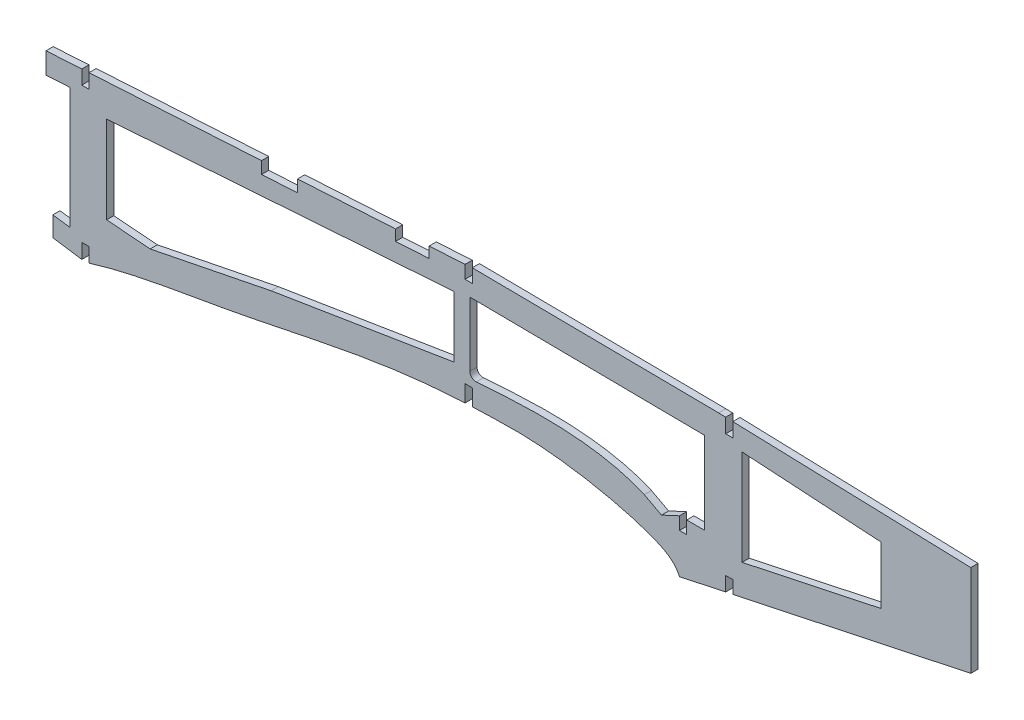
SolidWorks part; units mm, degrees
ref_plane "Front Plane" through (0, 0, 0) normal (0, 0, 1) x (1, 0, 0)
ref_plane "Top Plane" through (0, 0, 0) normal (0, 1, 0) x (1, 0, 0)
ref_plane "Right Plane" through (0, 0, 0) normal (1, 0, 0) x (0, 0, -1)
sketch "Sketch1" plane through (0, 0, 0) normal (0, 0, 1) x (1, 0, 0)
  line L0 (0, 0) -> (110, 0) construction
  line L1 (110, 0) -> (110, 21) construction
  line L2 (0, 0) -> (110, 21)
  line L3 (23.5, 17.3139) -> (20, 16.6457)
  line L4 (0, 0) -> (20, 0)
  line L5 (20, 0) -> (20, 67.15) construction
  line L6 (0, 0) -> (0, 67.15) construction
  line L7 (0, 67.15) -> (110, 67.15) construction
  line L8 (110, 61.55) -> (110, 67.15)
  line L9 (0, 67.15) -> (110, 61.55)
  line L10 (23.5, 53.9381) -> (81.5, 50.9854)
  line L11 (81.5, 50.9854) -> (81.5, 28.3866)
  line L12 (23.5, 53.9381) -> (23.5, 17.3139)
  line L13 (23.5, 17.3139) -> (81.5, 28.3866)
  line L14 (110, 21) -> (110, 61.55) construction
  line L15 (112, 61.4482) -> (112, 21.3818)
  line L16 (110, 61.55) -> (112, 61.4482)
  line L17 (110, 21) -> (112, 21.3818)
  line L18 (10.9, 67.15) -> (10.9, 0)
  line L19 (0, 67.15) -> (-82.3902, 71.3444)
  line L20 (0, 0) -> (-182.0672, -34.7583)
  line L21 (-86.7, -36.2944) -> (-86.7, -57.7944)
  line L22 (-93.05, 89.1409) -> (-93.05, -40.6456)
  line L23 (-70.5516, 60.184) -> (7.4462, 55.0566)
  line L24 (-89.4413, 54.3923) -> (-89.4413, 37.6042)
  line L25 (-65.3332, 22.0194) -> (-42.2468, 20.2821) construction
  line L26 (-42.2468, 20.2821) -> (-21.4079, 14.5616) construction
  line L27 (-21.4079, 14.5616) -> (-8.5368, 8.8411) construction
  line L28 (-8.5368, 8.8411) -> (-2.8162, 7.0023) construction
  line L29 (-2.8162, 7.0023) -> (0, 0) construction
  line L30 (-235.9653, 18.0968) -> (-234.0715, 53.1142)
  line L31 (-238.05, 59.4719) -> (-238.05, 21) construction
  line L32 (-921.7383, -124.7627) -> (144.2786, -161.9889) construction
  line L34 (-226.3459, 60.184) -> (-104.3294, 60.184)
  line L35 (-82.0567, 37.6042) -> (-82.7237, 57.9466)
  line L36 (-82.3902, 71.3444) -> (-103.6, 72.4242)
  line L37 (-103.6, 72.4242) -> (-103.6, 67.1242)
  line L38 (-103.6, 67.1242) -> (-117.6, 67.1242)
  line L39 (-117.6, 67.1242) -> (-117.6, 72.6011)
  line L40 (-117.6, 72.6011) -> (-158.5, 72.6011)
  line L41 (-158.5, 72.6011) -> (-158.5, 68.6011)
  line L42 (-158.5, 68.6011) -> (-173.5, 69.3647)
  line L43 (-173.5, 69.3647) -> (-173.5, 73.3311)
  line L44 (-173.5, 73.3311) -> (-250.6778, 73.3311)
  line L45 (-250.6778, 73.3311) -> (-251.1351, 64.35)
  line L46 (-251.1351, 64.35) -> (-249.1426, 59.4719)
  line L47 (-249.1426, 59.4719) -> (-253.0614, 11.9612)
  spline_without_curve S0
  spline S1 degree 3 poles (-62.7428, 33.1676) (-50.008, 31.9642) (-31.0962, 32.5015) (-14.1751, 24.9914) (-9.6822, 22.192) knots 0 0 0 0 0.709755 1 1 1 1
  spline S2 degree 3 poles (-9.6822, 22.192) (-6.8917, 20.9668) (-4.0654, 23.2801) (1.077, 24.0309) (6.7349, 23.1276) (13.0796, 25.9871) (10.9, 30.3114) knots 0 0 0 0 0.304362 0.391412 0.603771 1 1 1 1
  spline S3 degree 3 poles (-65.3332, 22.0194) (-77.4805, 22.6509) (-98.8967, 23.1079) (-139.7694, 19.7032) (-187.7649, 10.9991) (-227.3069, 7.5749) (-246.6861, 2.6333) knots 0 0 0 0 0.199692 0.351003 0.672194 1 1 1 1
  spline S4 degree 3 poles (-62.7428, 33.1676) (-67.9368, 33.6388) (-74.1452, 31.6619) (-82.8627, 34.4448) (-82.0567, 37.6042) knots 0 0 0 0 0.65977 1 1 1 1
  spline S5 degree 3 poles (-104.3294, 60.184) (-100.5301, 59.5513) (-93.8007, 61.9485) (-88.7866, 56.5953) (-89.4413, 54.3923) knots 0 0 0 0 0.661964 1 1 1 1
  spline S6 degree 3 poles (-104.3294, 33.547) (-100.6826, 33.3941) (-97.3824, 32.6768) (-91.1309, 33.381) (-89.6784, 34.473) (-89.4413, 37.6042) knots 0 0 0 0 0.555991 0.846219 1 1 1 1
  spline S7 degree 3 poles (-104.3294, 33.547) (-116.4931, 34.3961) (-139.9294, 30.8214) (-169.9623, 27.1478) (-193.8607, 26.9431) (-204.0402, 24.0023) (-211.1217, 23.2564) (-214.8026, 19.376) (-215.2918, 15.9456) (-214.9447, 14.6164) (-218.1891, 14.6988) (-221.7312, 14.9192) (-230.6867, 16.3937) (-236.4685, 15.9971) (-235.9653, 18.0968) knots 0 0 0 0 0.241116 0.431915 0.666521 0.747659 0.783153 0.799752 0.821748 0.858269 0.866885 0.907914 0.932706 1 1 1 1
  spline S8 degree 3 poles (-82.7237, 57.9466) (-82.8248, 63.2577) (-71.0235, 59.3637) (-70.5516, 60.184) knots 0 0 0 0 1 1 1 1
  spline S9 degree 2 poles (7.4462, 55.0566) (12.5645, 55.8042) (10.9, 50.909) knots 0 0 0 1 1 1
  spline S10 degree 3 poles (-234.0715, 53.1142) (-234.3359, 55.4474) (-232.0516, 60.1047) (-228.0459, 60.2249) (-226.3459, 60.184) knots 0 0 0 0 0.618254 1 1 1 1
  spline S11 degree 2 poles (-253.0614, 11.9612) (-252.6953, 7.068) (-247.464, 8.0018) knots 0 0 0 1 1 1
  spline S12 degree 3 poles (-246.6861, 2.6333) (-248.9283, 3.1544) (-247.5659, 6.6016) (-247.464, 8.0018) knots 0 0 0 0 1 1 1 1
  point P55 (-93.05, 46.4253)
  dimension "D1" = 110
  dimension "D2" = 21
  dimension "D3" = 12.6
  dimension "D4" = 20
  dimension "D5" = 67.15
  dimension "D6" = 5.6
  dimension "D7" = 110
  dimension "D8" = 12
  dimension "D9" = 3.5
  dimension "D10" = 58
  dimension "D11" = 2
  dimension "D12" = 12.6
  dimension "D13" = 97.6
  dimension "D14" = 6.35
  dimension "D15" = 14
  dimension "D16" = 145
  dimension "D17" = 15
  dimension "D18" = 40.9
  dimension "D19" = 10.55
  dimension "D20" = 5.3
  dimension "D21" = 4
sketch "Sketch2" plane through (0, 0, 0) normal (0, 0, 1) x (1, 0, 0)
  line L0 (0, 0) -> (110, 21) construction
  line L1 (0, 0) -> (110, 21)
  line L2 (112, 61.4482) -> (112, 21.3818) construction
  line L3 (112, 61.4482) -> (112, 21.3818)
  line L4 (-70.5516, 60.184) -> (7.4462, 55.0566) construction
  line L5 (110, 21) -> (112, 21.3818) construction
  line L6 (110, 21) -> (112, 21.3818)
  line L7 (110, 61.55) -> (112, 61.4482) construction
  line L8 (110, 61.55) -> (112, 61.4482)
  line L9 (0, 67.15) -> (110, 61.55) construction
  line L10 (0, 67.15) -> (110, 61.55)
  line L11 (0, 67.15) -> (-82.3902, 71.3444) construction
  line L12 (0, 67.15) -> (-82.3902, 71.3444)
  line L13 (-82.3902, 71.3444) -> (-103.6, 72.4242) construction
  line L14 (-82.3902, 71.3444) -> (-103.6, 72.4242)
  line L15 (-103.6, 72.4242) -> (-103.6, 67.3782)
  line L16 (-103.6, 67.3782) -> (-117.6, 67.3782)
  line L17 (-117.6, 67.3782) -> (-117.6, 72.6011)
  line L18 (-117.6, 72.6011) -> (-158.5, 72.6011)
  line L19 (-158.5, 72.6011) -> (-158.5, 69.3647)
  line L20 (-158.5, 69.3647) -> (-173.5, 69.3647)
  line L21 (-173.5, 69.3647) -> (-173.5, 73.3311)
  line L22 (-173.5, 73.3311) -> (-250.6778, 73.3311) construction
  line L23 (-173.5, 73.3311) -> (-250.6778, 73.3311)
  line L24 (-250.6778, 73.3311) -> (-253.0614, 11.9612)
  line L25 (-89.4413, 54.3923) -> (-89.4413, 37.6042) construction
  line L26 (-226.3459, 60.184) -> (-104.3294, 60.184) construction
  line L27 (-235.9653, 18.0968) -> (-234.0715, 53.1142) construction
  line L28 (-89.4413, 54.3923) -> (-89.4413, 37.6042)
  line L29 (-226.3459, 60.184) -> (-104.3294, 60.184)
  line L30 (-235.9653, 18.0968) -> (-234.0715, 53.1142)
  line L31 (-82.0567, 37.6042) -> (-82.7237, 57.9466) construction
  line L32 (-70.5516, 60.184) -> (7.4462, 55.0566)
  line L33 (-82.0567, 37.6042) -> (-82.7237, 57.9466)
  line L34 (10.9, 50.909) -> (10.9, 30.3114)
  line L35 (81.5, 50.9854) -> (81.5, 28.3866) construction
  line L36 (23.5, 17.3139) -> (81.5, 28.3866) construction
  line L37 (23.5, 53.9381) -> (81.5, 50.9854) construction
  line L38 (23.5, 53.9381) -> (23.5, 17.3139) construction
  line L39 (81.5, 48.1342) -> (81.5, 30.8681)
  line L40 (27.0626, 17.994) -> (79.0626, 27.9213)
  line L41 (26.6525, 53.7776) -> (78.6525, 51.1303)
  line L42 (23.5, 50.7815) -> (23.5, 20.9408)
  line L43 (-158.5, 72.6011) -> (-158.5, 68.6011) construction
  arc A0 (26.6525, 53.7776) -> (23.5, 50.7815) centre (26.5, 50.7815) ccw
  arc A1 (27.0626, 17.994) -> (23.5, 20.9408) centre (26.5, 20.9408) cw
  arc A2 (81.5, 30.8681) -> (79.0626, 27.9213) centre (78.5, 30.8681) cw
  arc A3 (81.5, 48.1342) -> (78.6525, 51.1303) centre (78.5, 48.1342) ccw
  parabola Q0 (-253.0614, 11.9612) -> (-247.464, 8.0018) focus (-250.6889, 9.8561) apex (-251.6748, 8.6753) construction
  parabola Q1 (-253.0614, 11.9612) -> (-247.464, 8.0018) focus (-250.6889, 9.8561) apex (-251.6748, 8.6753)
  parabola Q2 (7.4462, 55.0566) -> (10.9, 50.909) focus (10.2347, 53.865) apex (10.8693, 54.3929) construction
  parabola Q3 (7.4462, 55.0566) -> (10.9, 50.909) focus (10.2347, 53.865) apex (10.8693, 54.3929)
  spline S0 degree 3 poles (1215.9924, 1366.2087) (-1689.2719, -1445.9602) (1160.7038, 1491.2702) (-1612.7605, -1453.4516) knots -5.972872 -5.972872 -5.972872 -5.972872 7.300913 7.300913 7.300913 7.300913 only from (-246.6861, 2.6333) to (-247.464, 8.0018) construction
  spline S1 degree 3 poles (-246.6861, 2.6333) (-248.9283, 3.1544) (-247.5659, 6.6016) (-247.464, 8.0018) knots 0 0 0 0 1 1 1 1
  spline S2 degree 3 poles (175.3636, 1967.872) (391.9741, -245.9956) (130.7811, 42.2402) (-139.7694, 19.7032) (-325.1272, -13.9116) (-514.1452, 28.671) (-309.5796, -1983.4136) knots -3.777296 -3.777296 -3.777296 -3.777296 0.199692 0.351003 0.672194 3.290466 3.290466 3.290466 3.290466 only from (-65.3332, 22.0194) to (-246.6861, 2.6333) construction
  spline S3 degree 3 poles (-65.3332, 22.0194) (-77.4805, 22.6509) (-98.8967, 23.1079) (-139.7694, 19.7032) (-187.7649, 10.9991) (-227.3069, 7.5749) (-246.6861, 2.6333) knots 0 0 0 0 0.199692 0.351003 0.672194 1 1 1 1
  spline S4 degree 5 poles (1876.0426, 360.0904) (-1729.8867, -1179.746) (583.5253, 1803.2982) (78.4446, -2000.9415) (-313.5377, 2017.6127) (349.0217, -1969.1752) knots -2.469726 -2.469726 -2.469726 -2.469726 -2.469726 -2.469726 2.883008 2.883008 2.883008 2.883008 2.883008 2.883008 only from (-65.3332, 22.0194) to (0, 0) construction
  spline S5 degree 5 poles (-65.3332, 22.0194) (-42.2468, 20.2821) (-21.4079, 14.5616) (-8.5368, 8.8411) (-2.8162, 7.0023) (0, 0) knots 0 0 0 0 0 0 1 1 1 1 1 1
  spline S6 degree 3 poles (-2003.4226, -592.8129) (-74.6134, 83.2569) (-127.2178, 29.3158) (-83.3934, 34.2526) (-91.8628, 46.616) (-191.2637, 2034.7775) knots -4.772522 -4.772522 -4.772522 -4.772522 0.555991 0.846219 2.237697 2.237697 2.237697 2.237697 only from (-104.3294, 33.547) to (-89.4413, 37.6042) construction
  spline S7 degree 3 poles (-884.1428, -1800.4231) (147.9483, 84.9453) (-58.8059, 40.7444) (-169.9623, 27.1478) (-193.8607, 26.9431) (-204.0402, 24.0023) (-211.1217, 23.2564) (-214.8026, 19.376) (-215.2918, 15.9456) (-214.9447, 14.6164) (-218.1891, 14.6988) (-221.7312, 14.9192) (-259.045, 21.0628) (-280.7399, -17.3172) (1437.9042, 1112.0112) knots -1.800378 -1.800378 -1.800378 -1.800378 0.241116 0.431915 0.666521 0.747659 0.783153 0.799752 0.821748 0.858269 0.866885 0.907914 0.932706 1.421519 1.421519 1.421519 1.421519 only from (-104.3294, 33.547) to (-235.9653, 18.0968) construction
  spline S8 degree 3 poles (879.86, 1711.5652) (-207.6215, -132.0929) (-295.8251, 232.0271) (-122.4858, -93.2389) (-314.6686, 2056.7417) knots -5.484197 -5.484197 -5.484197 -5.484197 0.618254 6.842445 6.842445 6.842445 6.842445 only from (-234.0715, 53.1142) to (-226.3459, 60.184) construction
  spline S9 degree 3 poles (-104.3294, 33.547) (-100.6826, 33.3941) (-97.3824, 32.6768) (-91.1309, 33.381) (-89.6784, 34.473) (-89.4413, 37.6042) knots 0 0 0 0 0.555991 0.846219 1 1 1 1
  spline S10 degree 3 poles (-104.3294, 33.547) (-116.4931, 34.3961) (-139.9294, 30.8214) (-169.9623, 27.1478) (-193.8607, 26.9431) (-204.0402, 24.0023) (-211.1217, 23.2564) (-214.8026, 19.376) (-215.2918, 15.9456) (-214.9447, 14.6164) (-218.1891, 14.6988) (-221.7312, 14.9192) (-230.6867, 16.3937) (-236.4685, 15.9971) (-235.9653, 18.0968) knots 0 0 0 0 0.241116 0.431915 0.666521 0.747659 0.783153 0.799752 0.821748 0.858269 0.866885 0.907914 0.932706 1 1 1 1
  spline S11 degree 3 poles (-234.0715, 53.1142) (-234.3359, 55.4474) (-232.0516, 60.1047) (-228.0459, 60.2249) (-226.3459, 60.184) knots 0 0 0 0 0.618254 1 1 1 1
  spline S12 degree 3 poles (319.5224, 2014.3086) (-192.9155, -111.4852) (-73.7068, 193.2347) (-74.1309, -42.5933) (-2079.8517, 234.6153) knots -4.398535 -4.398535 -4.398535 -4.398535 0.661964 3.952777 3.952777 3.952777 3.952777 only from (-104.3294, 60.184) to (-89.4413, 54.3923) construction
  spline S13 degree 3 poles (-104.3294, 60.184) (-100.5301, 59.5513) (-93.8007, 61.9485) (-88.7866, 56.5953) (-89.4413, 54.3923) knots 0 0 0 0 0.661964 1 1 1 1
  spline S14 degree 3 poles (-476.921, 1966.6082) (-22.6367, -59.8265) (-22.4132, 20.601) (1.077, 24.0309) (25.1351, 20.1898) (79.5245, 97.6802) (-1928.1805, 515.6228) knots -2.154256 -2.154256 -2.154256 -2.154256 0.304362 0.391412 0.603771 3.262307 3.262307 3.262307 3.262307 only from (-9.6822, 22.192) to (10.9, 30.3114) construction
  spline S15 degree 3 poles (290.3742, 1996.6931) (-276.3479, -157.1226) (45.2421, 284.1781) (112.1059, -304.2564) (-1943.388, -409.2218) knots -4.781032 -4.781032 -4.781032 -4.781032 0.709755 6.530859 6.530859 6.530859 6.530859 only from (-62.7428, 33.1676) to (-9.6822, 22.192) construction
  spline S16 degree 3 poles (1014.7339, -1650.8552) (-65.1434, 157.9827) (-20.1321, -37.6544) (-136.3103, 72.496) (1711.8022, 920.8151) knots -4.712693 -4.712693 -4.712693 -4.712693 0.65977 3.302586 3.302586 3.302586 3.302586 only from (-62.7428, 33.1676) to (-82.0567, 37.6042) construction
  spline S17 degree 3 poles (1566.4817, -1072.7309) (-1852.9005, 1150.0589) (1734.6604, -974.3467) (-1819.0286, 1030.9337) knots -3.685572 -3.685572 -3.685572 -3.685572 4.790703 4.790703 4.790703 4.790703 only from (-82.7237, 57.9466) to (-70.5516, 60.184) construction
  spline S18 degree 3 poles (-9.6822, 22.192) (-6.8917, 20.9668) (-4.0654, 23.2801) (1.077, 24.0309) (6.7349, 23.1276) (13.0796, 25.9871) (10.9, 30.3114) knots 0 0 0 0 0.304362 0.391412 0.603771 1 1 1 1
  spline S19 degree 3 poles (-62.7428, 33.1676) (-50.008, 31.9642) (-31.0962, 32.5015) (-14.1751, 24.9914) (-9.6822, 22.192) knots 0 0 0 0 0.709755 1 1 1 1
  spline S20 degree 3 poles (-62.7428, 33.1676) (-67.9368, 33.6388) (-74.1452, 31.6619) (-82.8627, 34.4448) (-82.0567, 37.6042) knots 0 0 0 0 0.65977 1 1 1 1
  spline S21 degree 3 poles (-82.7237, 57.9466) (-82.8248, 63.2577) (-71.0235, 59.3637) (-70.5516, 60.184) knots 0 0 0 0 1 1 1 1
  point P6 (-2.1894, 23.46)
  dimension "D1" = 3
  dimension "D2" = 3
  dimension "D3" = 14
sketch "Sketch3" plane through (0, 0, 0) normal (0, 0, -1) x (-1, 0, 0)
  line L0 (-20, 0) -> (-20, 67.15) construction
  line L1 (-20, 0) -> (-20, 67.15)
  line L2 (0, 67.15) -> (-110, 61.55) construction
  line L3 (0, 23.8107) -> (0, -7.1001) construction
  line L4 (0, 67.15) -> (-110, 61.55)
  line L5 (-17, 66.2845) -> (-17, 60.5845)
  line L6 (-17, 60.5845) -> (-20, 60.5845)
  line L7 (-20, 60.5845) -> (-20, 66.1318)
  line L8 (-20, 66.1318) -> (-17, 66.2845)
  line L9 (0, 0) -> (-110, 21) construction
  line L10 (0, 0) -> (-110, 21)
  line L11 (-17, 8.7455) -> (-17, 3.2455)
  line L12 (-17, 8.7455) -> (-20, 8.7455)
  line L13 (-20, 8.7455) -> (-20, 3.7748)
  line L14 (-20, 3.7748) -> (-17, 3.2455)
  line L15 (88, 71.63) -> (88, 66.2827)
  line L16 (91, 71.7827) -> (91, 66.2827)
  line L17 (82.3902, 71.3444) -> (103.6, 72.4242) construction
  line L18 (91, 66.2827) -> (88, 66.2827)
  line L19 (88, 71.63) -> (91, 71.7827)
  line L24 (0, 23.8107) -> (0, 17.8107)
  line L25 (-3, 23.7752) -> (-3, 17.8107)
  line L26 (0, 17.8107) -> (-3, 17.8107)
  line L27 (-3, 23.7752) -> (0, 23.8107)
  line L28 (88, 160.3101) -> (88, -51.3247)
  line L30 (91, 29.1781) -> (91, 22.6781)
  line L31 (91, 29.1781) -> (88, 29.1781)
  line L32 (88, 29.1781) -> (88, 22.6781)
  line L33 (88, 22.6781) -> (91, 22.6781)
  spline S1 degree 3 poles (9.6822, 22.192) (6.8917, 20.9668) (4.0654, 23.2801) (-1.077, 24.0309) (-6.7349, 23.1276) (-13.0796, 25.9871) (-10.9, 30.3114) knots 0 0 0 0 0.304362 0.391412 0.603771 1 1 1 1 construction
  spline S2 degree 3 poles (65.3332, 22.0194) (77.4805, 22.6509) (98.8967, 23.1079) (139.7694, 19.7032) (187.7649, 10.9991) (227.3069, 7.5749) (246.6861, 2.6333) knots 0 0 0 0 0.199692 0.351003 0.672194 1 1 1 1 construction
  dimension "D1" = 3
  dimension "D2" = 5.7
  dimension "D3" = 5.5
  dimension "D4" = 6.5
  dimension "D5" = 3
  dimension "D6" = 5.5
  dimension "D7" = 108
  dimension "D8" = 20
  dimension "D9" = 6
  dimension "D10" = 3
sketch "Sketch4" plane through (0, 0, 0) normal (0, 0, -1) x (-1, 0, 0)
  line L0 (119.2548, -0.35) -> (-119.2548, -0.35)
  line L1 (0, -0.35) -> (0, 67.15)
  line L57 (253.3406, -1.2994) -> (254.1722, 60.1111)
  line L58 (254.1722, 60.1111) -> (174.8745, 64.2669)
  line L59 (174.8745, 64.2669) -> (174.8979, 65.3912)
  line L60 (174.8979, 65.3912) -> (159.85, 57.5564)
  line L61 (159.85, 57.5564) -> (159.9757, 68.9387)
  line L62 (159.9757, 68.9387) -> (119.0846, 69.7894)
  line L63 (119.0846, 69.7894) -> (118.9759, 64.5677)
  line L64 (118.9759, 64.5677) -> (104.979, 64.8589)
  line L65 (104.979, 64.8589) -> (105.0839, 69.9038)
  line L66 (105.0839, 69.9038) -> (89.4708, 69.4342)
  line L70 (89.4708, 69.4342) -> (-15.6177, 66.2738)
  line L74 (-15.6177, 66.2738) -> (-110.6977, 63.4144)
  line L75 (-110.6977, 63.4144) -> (-111.5311, 23.3567)
  line L76 (-111.5311, 23.3567) -> (0, -0.35)
  parabola Q2 (247.5437, -4.9604) -> (253.3406, -1.2994) focus (250.8611, -3.2775) apex (251.7839, -4.5082)
  spline S8 degree 3 poles (66.396, 18.2199) (74.9521, 18.2164) (83.5166, 18.0283) (92.0622, 17.5345) knots 0.875946 0.875946 0.875946 0.875946 1.016409 1.016409 1.016409 1.016409
  spline S9 degree 3 poles (92.0622, 17.5345) (95.666, 17.3341) (108.4649, 16.4288) (140.621, 12.1175) (188.1196, 1.0175) (227.4402, -4.3854) (246.5472, -10.2927) knots 0 0 0 0 0.059228 0.210539 0.53173 0.859537 0.859537 0.859537 0.859537
  spline S10 degree 3 poles (246.5472, -10.2927) (248.8088, -9.8636) (247.5883, -6.3636) (247.5437, -4.9604) knots 0 0 0 0 1 1 1 1
  spline S11 degree 5 poles (0, -0.35) (3.1789, 6.4953) (8.9878, 8.0322) (22.1406, 13.0712) (43.2504, 17.6932) (66.396, 18.2199) knots 0 0 0 0 0 0 1 1 1 1 1 1
  point P0 (159.85, 57.5564)
  point P3 (0, -0.35)
  point P4 (0, -0.35)
  point P15 (0, 0)
  dimension "D1" = 12
  dimension "D2" = 67.5
sketch "Sketch6" plane through (0, 0, -3) normal (0, 0, -1) x (-1, 0, 0)
  line L0 (0, -81.2122) -> (0, 80.5122) construction
  line L1 (-10.5, 55.95) -> (87.47, 56.9492)
  line L2 (-10.5, 55.95) -> (-10.5, 21.65)
  line L3 (-3, 21.65) -> (-10.5, 21.65)
  line L4 (0, 21.65) -> (0, 16.35)
  line L5 (0, 16.35) -> (-3, 16.35)
  line L6 (-3, 21.65) -> (-3, 16.35)
  line L7 (0, 21.65) -> (7.5224, 18.1423)
  line L8 (7.5224, 18.1423) -> (14.7017, 21.9596)
  line L9 (87.47, 56.9492) -> (87.47, 30.1297)
  line L10 (87.47, 27.441) -> (87.47, 17.771) construction
  line L11 (78.3036, 17.771) -> (96.6364, 17.771) construction
  line L12 (0, -0.35) -> (-19.25, 3.7417)
  line L13 (104.45, 66.8886) -> (104.45, 62.3808)
  line L14 (-16.3334, 66.995) -> (86.45, 68.0433)
  line L15 (-26.1, 57.7585) -> (-26.1, 17.8747)
  line L16 (-111.5311, 23.3567) -> (0, -0.35) construction
  line L17 (-19.25, 66.904) -> (-19.25, 60.904)
  line L18 (-111.5311, 23.3567) -> (-22.25, 4.3794)
  line L19 (118.45, 66.0678) -> (118.45, 61.5601)
  line L21 (-19.25, 9.7417) -> (-19.25, 3.7417)
  line L25 (-19.25, 66.904) -> (-19.25, 60.904)
  line L26 (-19.25, 60.904) -> (-22.25, 60.904)
  line L27 (-22.25, 66.8105) -> (-22.25, 60.904)
  line L29 (86.45, 82.6833) -> (86.45, 9.104) construction
  line L30 (104.45, 62.3808) -> (118.45, 61.5601)
  line L32 (86.45, 68.0433) -> (86.45, 62.3703)
  line L33 (86.45, 62.3703) -> (89.45, 62.3703)
  line L34 (89.45, 67.768) -> (89.45, 62.3703)
  line L35 (86.45, 17.6703) -> (89.45, 17.6703)
  line L36 (86.45, 17.6703) -> (86.45, 24.6703)
  line L37 (86.45, 24.6703) -> (89.45, 24.6703)
  line L38 (89.45, 17.6703) -> (89.45, 24.6703)
  line L39 (159.35, 63.6699) -> (159.35, 58.6614)
  line L40 (174.35, 62.7905) -> (174.35, 57.7819)
  line L41 (159.35, 58.6614) -> (174.35, 57.7819)
  line L42 (-16.3334, 66.995) -> (-19.25, 66.904)
  line L43 (93.97, 55.6703) -> (93.97, 30.1703)
  line L44 (238.97, 45.4839) -> (238.97, 9.104)
  line L45 (254.27, -1.2771) -> (254.27, 49.29)
  line L46 (238.97, 45.4839) -> (93.97, 55.6703)
  line L47 (238.97, 9.104) -> (220.8231, 7.6436)
  line L48 (220.8231, 7.6436) -> (170.3292, 17.771)
  line L49 (170.3292, 17.771) -> (93.97, 30.1703)
  line L50 (-26.1, 17.8747) -> (-84.1, 30.203)
  line L51 (-84.1, 30.203) -> (-84.1, 54.203)
  line L52 (-26.1, 57.7585) -> (-84.1, 54.203)
  line L53 (118.45, 66.0678) -> (159.35, 63.6699)
  line L54 (174.35, 62.7905) -> (246.35, 58.5694)
  line L55 (-19.25, 9.7417) -> (-19.25, 3.7417)
  line L56 (-19.25, 9.7417) -> (-22.25, 9.7417)
  line L57 (-22.25, 9.7417) -> (-22.25, 4.3794)
  line L58 (-22.25, 66.8105) -> (-111.5311, 64.0267)
  line L59 (254.27, 58.1051) -> (264.27, 57.5188)
  line L60 (89.45, 67.768) -> (254.27, 58.1051) construction
  line L61 (89.45, 67.768) -> (104.45, 66.8886)
  line L62 (246.35, 52.5694) -> (246.35, -10.2318) construction
  line L63 (246.35, -10.2318) -> (246.35, -4.2318)
  line L64 (264.27, 48.7037) -> (254.27, 49.29)
  line L66 (246.35, 58.5694) -> (246.35, 52.5694)
  line L67 (261.435, -0.35) -> (261.435, -8.6139)
  line L69 (254.27, -1.2771) -> (261.435, -0.35)
  line L70 (264.27, 57.5188) -> (264.27, 48.7037)
  line L71 (249.35, 58.3935) -> (249.35, 52.5694)
  line L72 (246.35, 52.5694) -> (249.35, 52.5694)
  line L73 (249.35, 58.3935) -> (254.27, 58.1051)
  line L74 (249.35, -4.2318) -> (249.35, -10.4223)
  line L75 (246.35, -4.2318) -> (249.35, -4.2318)
  line L76 (249.35, -10.4223) -> (261.435, -8.6139)
  line L77 (246.35, -10.2318) -> (246.35, -23.1088) construction
  line L78 (-111.5311, 64.0267) -> (-121.5262, 63.715)
  line L79 (-111.5311, 23.3567) -> (-121.5262, 25.4812)
  line L80 (-121.5262, 63.715) -> (-121.5262, 25.4812)
  arc A1 (84.7894, 27.6362) -> (87.47, 30.1297) centre (84.97, 30.1297) ccw
  spline S0 degree 3 poles (-77.6637, 1965.2461) (-403.1026, -225.9067) (-128.1526, 48.1531) (140.621, 12.1175) (324.0581, -30.7502) (514.9719, 2.2988) (209.7722, -1996.9316) knots -3.912695 -3.912695 -3.912695 -3.912695 0.059228 0.210539 0.53173 3.149975 3.149975 3.149975 3.149975 only from (92.0622, 17.5345) to (246.5472, -10.2927) construction
  spline S1 degree 3 poles (7.5224, 18.1423) (15.8431, 23.4586) (31.7661, 27.749) (54.2955, 29.2195) (70.8321, 28.623) (81.0266, 27.9088) (84.7894, 27.6362) knots 0 0 0 0 0.360279 0.59219 0.828481 0.967074 0.967074 0.967074 0.967074
  spline S2 degree 3 poles (-72.1435, 1973.9319) (-667.3868, -1967.4883) (657.6539, 2002.3942) (321.1173, -1939.6078) knots -2.901307 -2.901307 -2.901307 -2.901307 4.225484 4.225484 4.225484 4.225484 only from (66.396, 18.2199) to (92.0622, 17.5345) construction
  spline S3 degree 5 poles (-451.6238, -1948.659) (418.7135, 1998.167) (-183.0533, -1994.4986) (-488.3696, 1831.0433) (1665.7875, -1269.0189) (-1854.6198, 457.4284) knots -1.883035 -1.883035 -1.883035 -1.883035 -1.883035 -1.883035 3.469724 3.469724 3.469724 3.469724 3.469724 3.469724 only from (0, -0.35) to (66.396, 18.2199) construction
  spline S4 degree 5 poles (0, -0.35) (3.1789, 6.4953) (8.9878, 8.0322) (22.1406, 13.0712) (43.2504, 17.6932) (66.396, 18.2199) knots 0 0 0 0 0 0 1 1 1 1 1 1
  spline S5 degree 3 poles (66.396, 18.2199) (74.9521, 18.2164) (83.5166, 18.0283) (92.0622, 17.5345) knots 0.875946 0.875946 0.875946 0.875946 1.016409 1.016409 1.016409 1.016409
  spline S6 degree 3 poles (92.0622, 17.5345) (95.666, 17.3341) (108.4649, 16.4288) (140.621, 12.1175) (188.0527, 1.0331) (227.3036, -4.3666) (246.35, -10.2318) knots 0 0 0 0 0.059228 0.210539 0.53173 0.858409 0.858409 0.858409 0.858409
  spline S9 degree 3 poles (65.3332, 22.0194) (77.4805, 22.6509) (98.8967, 23.1079) (139.7694, 19.7032) (187.7649, 10.9991) (227.3069, 7.5749) (246.6861, 2.6333) knots 0 0 0 0 0.199692 0.351003 0.672194 1 1 1 1 construction
  point P4 (0, -0.35)
  point P27 (87.47, 17.771)
  point P63 (-121.8977, 26.9999)
  point P68 (238.97, 27.294)
  point P72 (254.27, 28.414)
  dimension "D5" = 34.3
  dimension "D12" = 5
  dimension "D1" = 22
  dimension "D2" = 3
  dimension "D3" = 5.3
  dimension "D4" = 10.5
  dimension "D6" = 25
  dimension "D7" = 8.3
  dimension "D8" = 28
  dimension "D9" = 97.97
  dimension "D10" = 18
  dimension "D11" = 9.67
  dimension "D13" = 87.47
  dimension "D14" = 8.75
  dimension "D15" = 3
  dimension "D16" = 6
  dimension "D17" = 1.7002
  dimension "D18" = 3
  dimension "D19" = 4.5
  dimension "D20" = 7
  dimension "D21" = 37.7
  dimension "D22" = 105.7
  dimension "D23" = 3
  dimension "D24" = 3
  dimension "D25" = 14
  dimension "D26" = 5
  dimension "D27" = 6
  dimension "D28" = 40.9
  dimension "D29" = 15
  dimension "D30" = 8.8
  dimension "D31" = 40.67
  dimension "D32" = 6.5
  dimension "D33" = 145
  dimension "D34" = 15.3
  dimension "D35" = 10
  dimension "D36" = 10
  dimension "D37" = 25.5
  dimension "D38" = 15.6
  dimension "D39" = 12.4
  dimension "D40" = 58
  dimension "D41" = 24
  dimension "D42" = 3.0126
  dimension "D43" = 72
  dimension "D44" = 6
  dimension "D45" = 3
  dimension "D46" = 3
extrude "Boss-Extrude2" add sketch "Sketch6" along normal blind 3
